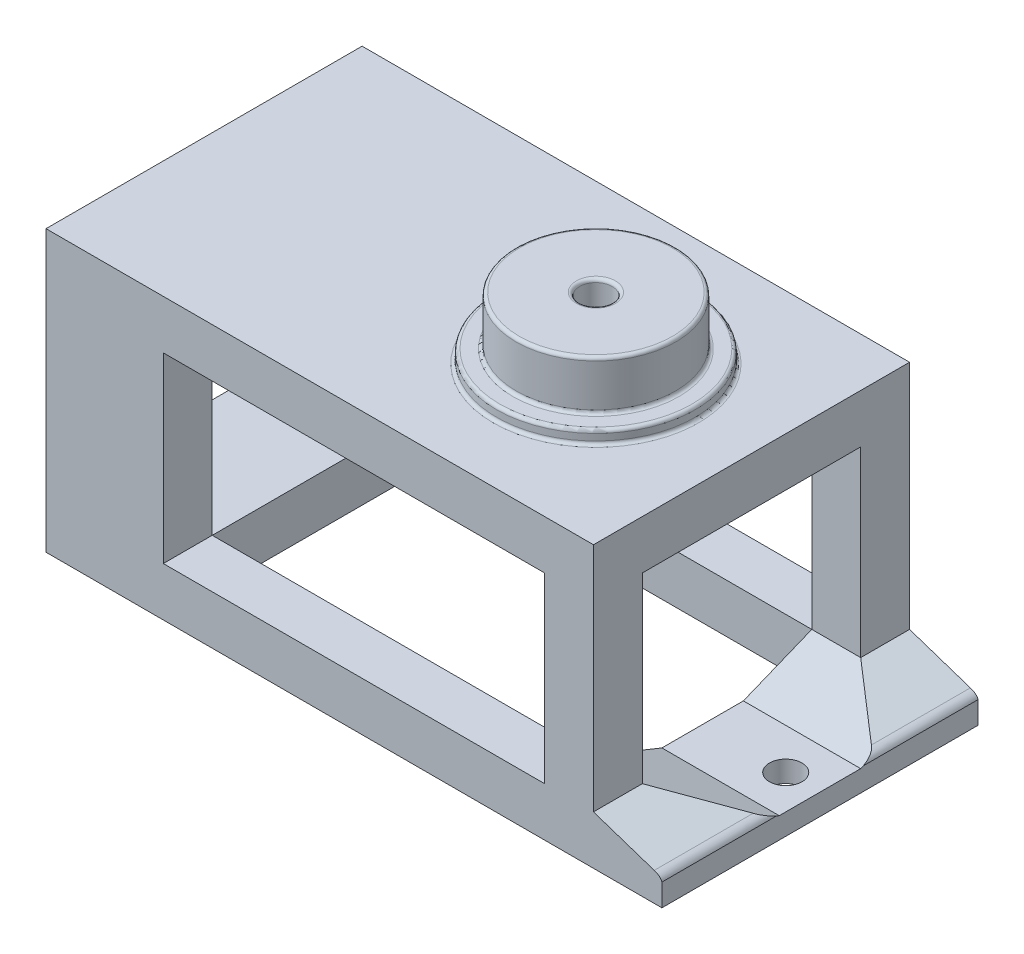
SolidWorks part; units mm, degrees
ref_plane "前视基准面" through (0, 0, 0) normal (0, 0, 1) x (1, 0, 0)
ref_plane "上视基准面" through (0, 0, 0) normal (0, 1, 0) x (1, 0, 0)
ref_plane "右视基准面" through (0, 0, 0) normal (1, 0, 0) x (0, 0, -1)
sketch "草图1" plane through (0, 0, 0) normal (0, 1, 0) x (1, 0, 0)
  line L1 (-11.7, 6.7) -> (11.7, 6.7)
  line L2 (-11.7, 6.7) -> (-11.7, -6.7)
  line L3 (-11.7, -6.7) -> (11.7, -6.7)
  line L4 (11.7, 6.7) -> (11.7, -6.7)
  line L5 (-11.7, 6.7) -> (11.7, -6.7) construction
  line L6 (-11.7, -6.7) -> (11.7, 6.7) construction
  line L7 (-14.7, 9.7) -> (14.7, 9.7)
  line L8 (-14.7, 9.7) -> (-14.7, -9.7)
  line L9 (-14.7, -9.7) -> (14.7, -9.7)
  line L10 (14.7, 9.7) -> (14.7, -9.7)
  line L11 (-14.7, 9.7) -> (14.7, -9.7) construction
  line L12 (-14.7, -9.7) -> (14.7, 9.7) construction
  point P0 (0, 0)
  point P6 (0, 0)
  dimension "D1" = 23.4
  dimension "D2" = 13.4
  dimension "D3" = 3
  dimension "D4" = 3
extrude "凸台-拉伸1" add sketch "草图1" along normal blind 16.4
sketch "草图2" plane through (0, 16.4, 0) normal (0, 1, 0) x (1, 0, 0)
  line L1 (-14.7, -9.7) -> (14.7, -9.7)
  line L2 (-14.7, -9.7) -> (-14.7, 9.7)
  line L3 (-14.7, 9.7) -> (14.7, 9.7)
  line L4 (14.7, -9.7) -> (14.7, 9.7)
  line L5 (-14.7, -9.7) -> (14.7, 9.7) construction
  line L6 (-14.7, 9.7) -> (14.7, -9.7) construction
  point P0 (0, 0)
extrude "凸台-拉伸2" add sketch "草图2" along normal blind 0.8
sketch "草图3" plane through (0, 17.2, 0) normal (0, 1, 0) x (1, 0, 0)
  line L0 (11.25, 0) -> (5.15, 0)
  line L1 (-11.25, 6.1) -> (11.25, 6.1)
  line L2 (-11.25, 6.1) -> (-11.25, -6.1)
  line L3 (-11.25, -6.1) -> (11.25, -6.1)
  line L4 (11.25, 6.1) -> (11.25, -6.1)
  line L5 (-11.25, 6.1) -> (11.25, -6.1) construction
  line L6 (-11.25, -6.1) -> (11.25, 6.1) construction
  circle A0 centre (5.15, 0) radius 6.1
  point P0 (0, 0)
  dimension "D1" = 22.5
  dimension "D2" = 12.2
extrude "凸台-拉伸3" add sketch "草图3" along normal blind 0.8
sketch "草图5" plane through (0, 18, 0) normal (0, 1, 0) x (1, 0, 0)
  circle A0 centre (5.15, 0) radius 4.9
  circle A1 centre (5.15, 0) radius 1
extrude "凸台-拉伸4" add sketch "草图5" along normal blind 3
fillet "圆角1" radius 0.2 6 edges at (5.15, 18, 6.1) (5.15, 21, 4.9) (5.15, 18, 4.9) (5.15, 17.2, 6.1) (5.15, 18, 1) (5.15, 21, 1)
sketch "草图6" plane through (0, 21, 0) normal (0, 1, 0) x (1, 0, 0)
sketch "草图7" plane through (-14.7, 0, 0) normal (-1, 0, 0) x (0, 0, 1)
  line L0 (9.7, 8.6) -> (-9.7, 8.6)
  line L1 (9.7, 17.2) -> (9.7, 0) construction
  line L2 (-9.7, 17.2) -> (-9.7, 0) construction
  line L3 (-9.7, 0) -> (9.7, 0) construction
  line L4 (6.7, 14.2) -> (-6.7, 14.2)
  line L5 (6.7, 14.2) -> (6.7, 3)
  line L6 (6.7, 3) -> (-6.7, 3)
  line L7 (-6.7, 14.2) -> (-6.7, 3)
  line L8 (6.7, 14.2) -> (-6.7, 3) construction
  line L9 (6.7, 3) -> (-6.7, 14.2) construction
  point P6 (0, 8.6)
  dimension "D1" = 3
  dimension "D2" = 3
extrude "切除-拉伸2" cut sketch "草图7" against normal blind 30 contours L4 L7 L0 L5 | L0 L7 L6 L5
sketch "草图8" plane through (0, 0, -9.7) normal (0, 0, -1) x (-1, 0, 0)
  line L0 (-14.7, 8.6) -> (14.7, 8.6)
  line L1 (-14.7, 17.2) -> (-14.7, 0) construction
  line L2 (14.7, 17.2) -> (14.7, 0) construction
  line L3 (-14.7, 17.2) -> (14.7, 17.2) construction
  line L4 (-11.7, 14.2) -> (11.7, 14.2)
  line L5 (-11.7, 14.2) -> (-11.7, 3)
  line L6 (-11.7, 3) -> (11.7, 3)
  line L7 (11.7, 14.2) -> (11.7, 3)
  line L8 (-11.7, 14.2) -> (11.7, 3) construction
  line L9 (-11.7, 3) -> (11.7, 14.2) construction
  point P6 (0, 8.6)
  dimension "D1" = 3
  dimension "D2" = 3
extrude "切除-拉伸3" cut sketch "草图8" against normal blind 30 contours L7 L4 L5 L0 | L7 L0 L5 L6
sketch "草图9" plane through (14.7, 0, 0) normal (1, 0, 0) x (0, 0, -1)
  line L1 (9.7, 0) -> (-9.7, 0)
  line L2 (9.7, 0) -> (9.7, 3)
  line L3 (9.7, 3) -> (-9.7, 3)
  line L4 (-9.7, 0) -> (-9.7, 3)
extrude "凸台-拉伸5" add sketch "草图9" along normal blind 4.2
sketch "草图10" plane through (0, 0, 9.7) normal (0, 0, 1) x (1, 0, 0)
  line L0 (18.9, 1.3692) -> (18.9, 1.6)
  line L1 (18.9, 3) -> (18.9, 0) construction
  line L2 (18.9, 3) -> (18.9, 1.6)
  line L3 (18.4866, 1.7378) -> (14.7, 3)
  line L4 (14.7, 3) -> (18.9, 3)
  spline S0 degree 2 poles (18.4297, 1.7568) (18.8199, 1.6361) (18.9, 1.3692) knots 0 0 0 0.659175 0.659175 0.659175
  line M6 (18.9, 0) -> (18.9, 3)
  line M7 (18.9, 3) -> (14.7, 3)
extrude "切除-拉伸4" cut sketch "草图10" against normal blind 20.2 contours L3 S0 M6 M7
sketch "草图11" plane through (14.7, 0, 0) normal (1, 0, 0) x (0, 0, -1)
  line L0 (6.7, 3) -> (-6.7, 3)
  line L1 (-9.7, 0) -> (9.7, 0) construction
  line L2 (6.7, 3) -> (-6.7, 3)
  line L3 (6.7, 3) -> (6.7, 1.3)
  line L4 (6.7, 1.3) -> (-6.7, 1.3)
  line L5 (-6.7, 3) -> (-6.7, 1.3)
  line L6 (2.5, 1.3) -> (-2.5, 1.3)
  line L7 (-2.5, 1.3) -> (-6.7, 3)
  line L8 (2.5, 1.3) -> (6.7, 3)
  point P11 (0, 1.3)
  dimension "D1" = 1.3
  dimension "D2" = 5
extrude "切除-拉伸5" cut sketch "草图11" along normal mid plane 10.2 contours L4 L8 L0 L7
sketch "草图12" plane through (0, 1.3, 0) normal (0, 1, 0) x (1, 0, 0)
  line L0 (18.9, 2.5) -> (11.7, 2.5) construction
  line L1 (18.9, -2.5) -> (14.7, -2.5)
  line L2 (18.9, -2.5) -> (18.9, 2.5)
  line L3 (18.9, 2.5) -> (14.7, 2.5)
  line L4 (14.7, -2.5) -> (14.7, 2.5)
  line L5 (14.7, -9.7) -> (14.7, 9.7) construction
  circle A0 centre (16.8, 0) radius 1
  dimension "D1" = 2
extrude "切除-拉伸6" cut sketch "草图12" against normal blind 2.2 contours A0
mirror "镜向1" about plane through (0, 0, 0) normal (1, 0, 0) of "凸台-拉伸5", "切除-拉伸6"
sketch "草图13" plane through (-14.7, 0, 0) normal (-1, 0, 0) x (0, 0, 1)
  line L0 (-6.7, 3) -> (-9.7, 3)
  line L1 (9.7, 17.2) -> (-9.7, 17.2)
  line L2 (9.7, 17.2) -> (9.7, 3)
  line L3 (9.7, 3) -> (6.7, 3)
  line L4 (-9.7, 17.2) -> (-9.7, 3)
  line L5 (6.7, 14.2) -> (-6.7, 14.2)
  line L6 (6.7, 14.2) -> (6.7, 3)
  line L8 (-6.7, 14.2) -> (-6.7, 3)
extrude "凸台-拉伸6" add sketch "草图13" along normal blind 4.2
